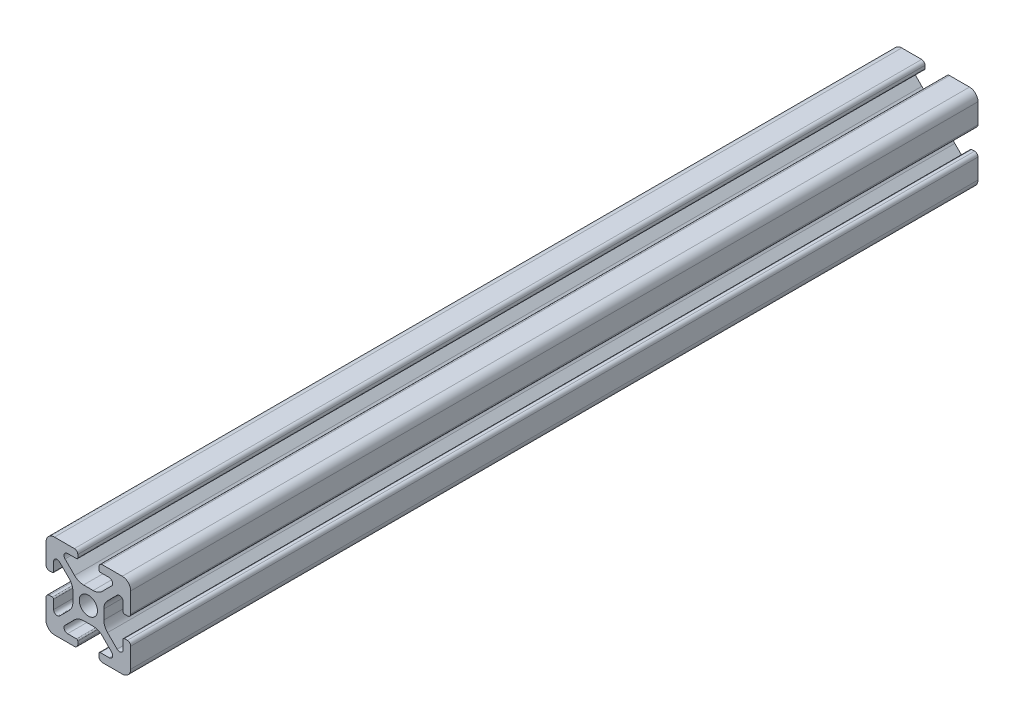
SolidWorks part; units mm, degrees
material "Alliage 1060"
ref_plane "Plan de face" through (0, 0, 0) normal (0, 0, 1) x (1, 0, 0)
ref_plane "Plan de dessus" through (0, 0, 0) normal (0, 1, 0) x (1, 0, 0)
ref_plane "Plan de droite" through (0, 0, 0) normal (1, 0, 0) x (0, 0, -1)
sketch "Esquisse1" plane through (0, 0, 0) normal (0, 0, 1) x (1, 0, 0)
  line L108 (-3.2559, 4.5287) -> (-5.5062, 6.779)
  line L109 (-4.9176, 8.2) -> (-2.8, 8.2)
  line L110 (-2.5, 8.5) -> (-2.5, 9.2)
  line L111 (-3.3, 10) -> (-8, 10)
  line L112 (-10, 8) -> (-10, 3.3)
  line L113 (-9.2, 2.5) -> (-8.5, 2.5)
  line L114 (-8.2, 2.8) -> (-8.2, 4.9176)
  line L115 (-6.779, 5.5062) -> (-4.5287, 3.2559)
  line L116 (-3.65, 1.1346) -> (-3.65, -1.1346)
  line L117 (-4.5287, -3.2559) -> (-6.779, -5.5062)
  line L118 (-8.2, -4.9176) -> (-8.2, -2.8)
  line L119 (-8.5, -2.5) -> (-9.2, -2.5)
  line L120 (-10, -3.3) -> (-10, -8)
  line L121 (-8, -10) -> (-3.3, -10)
  line L122 (-2.5, -9.2) -> (-2.5, -8.5)
  line L123 (-2.8, -8.2) -> (-4.9176, -8.2)
  line L124 (-5.5062, -6.779) -> (-3.2559, -4.5287)
  line L125 (-1.1346, -3.65) -> (1.1346, -3.65)
  line L126 (3.2559, -4.5287) -> (5.5062, -6.779)
  line L127 (4.9176, -8.2) -> (2.8, -8.2)
  line L128 (2.5, -8.5) -> (2.5, -9.2)
  line L129 (3.3, -10) -> (8, -10)
  line L130 (10, -8) -> (10, -3.3)
  line L131 (9.2, -2.5) -> (8.5, -2.5)
  line L132 (8.2, -2.8) -> (8.2, -4.9176)
  line L133 (6.779, -5.5062) -> (4.5287, -3.2559)
  line L134 (3.65, -1.1346) -> (3.65, 1.1346)
  line L135 (4.5287, 3.2559) -> (6.779, 5.5062)
  line L136 (8.2, 4.9176) -> (8.2, 2.8)
  line L137 (8.5, 2.5) -> (9.2, 2.5)
  line L138 (10, 3.3) -> (10, 8)
  line L139 (8, 10) -> (3.3, 10)
  line L140 (2.5, 9.2) -> (2.5, 8.5)
  line L141 (2.8, 8.2) -> (4.9176, 8.2)
  line L142 (5.5062, 6.779) -> (3.2559, 4.5287)
  line L143 (1.1346, 3.65) -> (-1.1346, 3.65)
  arc A42 (-2.15, 0) -> (2.15, 0) centre (0, 0) ccw
  arc A43 (2.15, 0) -> (-2.15, 0) centre (0, 0) ccw
  arc A108 (-4.9176, 8.2) -> (-5.5062, 6.779) centre (-4.9176, 7.3676) ccw
  arc A109 (-2.8, 8.2) -> (-2.5, 8.5) centre (-2.8, 8.5) ccw
  arc A110 (-2.5, 9.2) -> (-3.3, 10) centre (-3.3, 9.2) ccw
  arc A111 (-8, 10) -> (-10, 8) centre (-8, 8) ccw
  arc A112 (-10, 3.3) -> (-9.2, 2.5) centre (-9.2, 3.3) ccw
  arc A113 (-8.5, 2.5) -> (-8.2, 2.8) centre (-8.5, 2.8) ccw
  arc A114 (-6.779, 5.5062) -> (-8.2, 4.9176) centre (-7.3676, 4.9176) ccw
  arc A115 (-3.65, 1.1346) -> (-4.5287, 3.2559) centre (-6.65, 1.1346) ccw
  arc A116 (-4.5287, -3.2559) -> (-3.65, -1.1346) centre (-6.65, -1.1346) ccw
  arc A117 (-8.2, -4.9176) -> (-6.779, -5.5062) centre (-7.3676, -4.9176) ccw
  arc A118 (-8.2, -2.8) -> (-8.5, -2.5) centre (-8.5, -2.8) ccw
  arc A119 (-9.2, -2.5) -> (-10, -3.3) centre (-9.2, -3.3) ccw
  arc A120 (-10, -8) -> (-8, -10) centre (-8, -8) ccw
  arc A121 (-3.3, -10) -> (-2.5, -9.2) centre (-3.3, -9.2) ccw
  arc A122 (-2.5, -8.5) -> (-2.8, -8.2) centre (-2.8, -8.5) ccw
  arc A123 (-5.5062, -6.779) -> (-4.9176, -8.2) centre (-4.9176, -7.3676) ccw
  arc A124 (-1.1346, -3.65) -> (-3.2559, -4.5287) centre (-1.1346, -6.65) ccw
  arc A125 (3.2559, -4.5287) -> (1.1346, -3.65) centre (1.1346, -6.65) ccw
  arc A126 (4.9176, -8.2) -> (5.5062, -6.779) centre (4.9176, -7.3676) ccw
  arc A127 (2.8, -8.2) -> (2.5, -8.5) centre (2.8, -8.5) ccw
  arc A128 (2.5, -9.2) -> (3.3, -10) centre (3.3, -9.2) ccw
  arc A129 (8, -10) -> (10, -8) centre (8, -8) ccw
  arc A130 (10, -3.3) -> (9.2, -2.5) centre (9.2, -3.3) ccw
  arc A131 (8.5, -2.5) -> (8.2, -2.8) centre (8.5, -2.8) ccw
  arc A132 (6.779, -5.5062) -> (8.2, -4.9176) centre (7.3676, -4.9176) ccw
  arc A133 (3.65, -1.1346) -> (4.5287, -3.2559) centre (6.65, -1.1346) ccw
  arc A134 (4.5287, 3.2559) -> (3.65, 1.1346) centre (6.65, 1.1346) ccw
  arc A135 (8.2, 4.9176) -> (6.779, 5.5062) centre (7.3676, 4.9176) ccw
  arc A136 (8.2, 2.8) -> (8.5, 2.5) centre (8.5, 2.8) ccw
  arc A137 (9.2, 2.5) -> (10, 3.3) centre (9.2, 3.3) ccw
  arc A138 (10, 8) -> (8, 10) centre (8, 8) ccw
  arc A139 (3.3, 10) -> (2.5, 9.2) centre (3.3, 9.2) ccw
  arc A140 (2.5, 8.5) -> (2.8, 8.2) centre (2.8, 8.5) ccw
  arc A141 (5.5062, 6.779) -> (4.9176, 8.2) centre (4.9176, 7.3676) ccw
  arc A142 (1.1346, 3.65) -> (3.2559, 4.5287) centre (1.1346, 6.65) ccw
  arc A143 (-3.2559, 4.5287) -> (-1.1346, 3.65) centre (-1.1346, 6.65) ccw
extrude "Boss.-Extru.1" add sketch "Esquisse1" along normal blind 200
